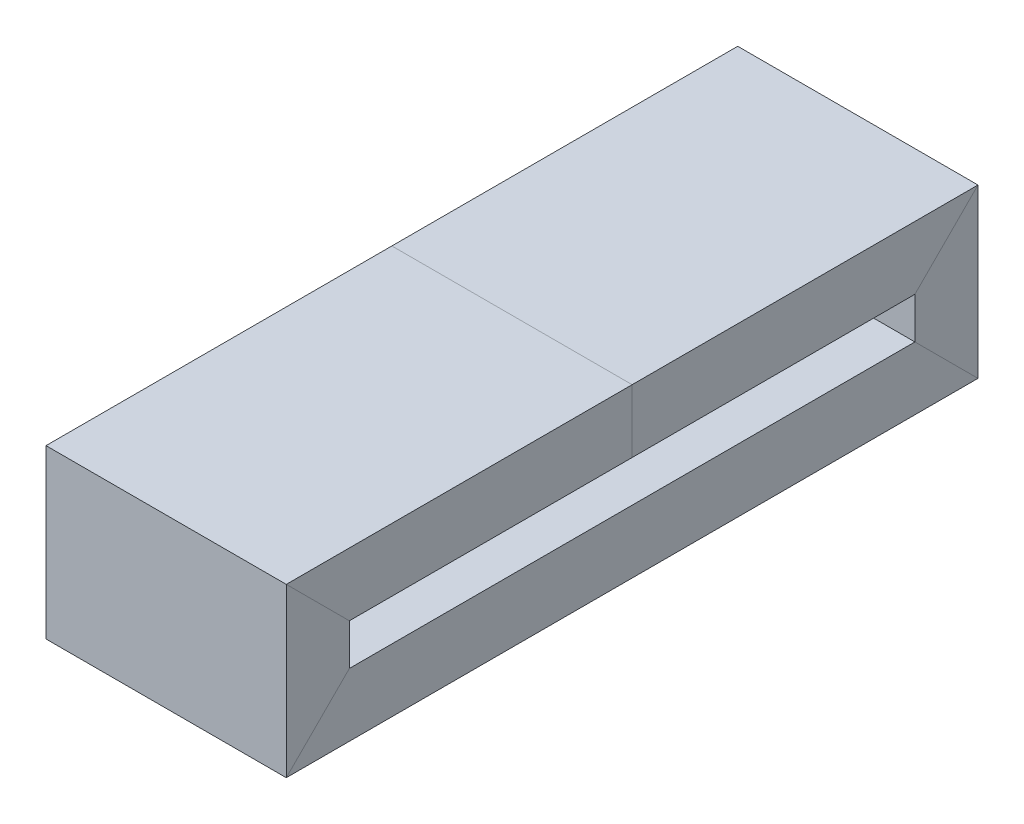
SolidWorks part; units mm, degrees
ref_plane "Front Plane" through (0, 0, 0) normal (0, 0, 1) x (1, 0, 0)
ref_plane "Top Plane" through (0, 0, 0) normal (0, 1, 0) x (1, 0, 0)
ref_plane "Right Plane" through (0, 0, 0) normal (1, 0, 0) x (0, 0, -1)
sketch "path" plane through (0, 0, 0) normal (1, 0, 0) x (0, 0, -1)
  line L0 (-127.2926, 0) -> (127.2926, 0) construction
  line L1 (0, -107.8773) -> (0, 107.8773) construction
  line L3 (-12.95, 2.15) -> (12.95, 2.15)
  line L4 (-12.95, 2.15) -> (-12.95, -2.15)
  line L5 (-12.95, -2.15) -> (12.95, -2.15)
  line L6 (12.95, 2.15) -> (12.95, -2.15)
  line L7 (-12.95, 2.15) -> (12.95, -2.15) construction
  line L8 (-12.95, -2.15) -> (12.95, 2.15) construction
  line L9 (-12.95, -0.8) -> (12.95, -0.8) construction
  line L10 (-12.95, -0.8) -> (-12.95, 0.8) construction
  line L11 (-12.95, 0.8) -> (12.95, 0.8) construction
  line L12 (12.95, -0.8) -> (12.95, 0.8) construction
  line L13 (-12.95, -0.8) -> (12.95, 0.8) construction
  line L14 (-12.95, 0.8) -> (12.95, -0.8) construction
  point P0 (0, 0)
  point P4 (0, 0)
  point P8 (0, 0)
  point P12 (0, 0)
  dimension "D1" = 25.9
  dimension "D2" = 4.3
  dimension "D3" = 1.6
sketch "cross-section" plane through (0, 0, 0) normal (0, 0, 1) x (1, 0, 0)
  line L0 (-76.524, 0) -> (76.524, 0) construction
  line L1 (0, -63.8176) -> (0, 63.8176) construction
  line L2 (0, -107.8773) -> (0, 107.8773) construction
  line L4 (-4.95, 0.85) -> (4.95, 0.85)
  line L5 (-4.95, 0.85) -> (-4.95, 3.45)
  line L6 (-4.95, 3.45) -> (4.95, 3.45)
  line L7 (4.95, 0.85) -> (4.95, 3.45)
  line L8 (-4.95, 0.85) -> (4.95, 3.45) construction
  line L9 (-4.95, 3.45) -> (4.95, 0.85) construction
  point P0 (0, 2.15)
  point P4 (0, 0)
  point P10 (0, 0)
  point P11 (0, 2.15)
  dimension "D1" = 2.15
  dimension "D2" = 9.9
  dimension "D3" = 2.6
sweep "Sweep1" add profiles "cross-section" path "path"
